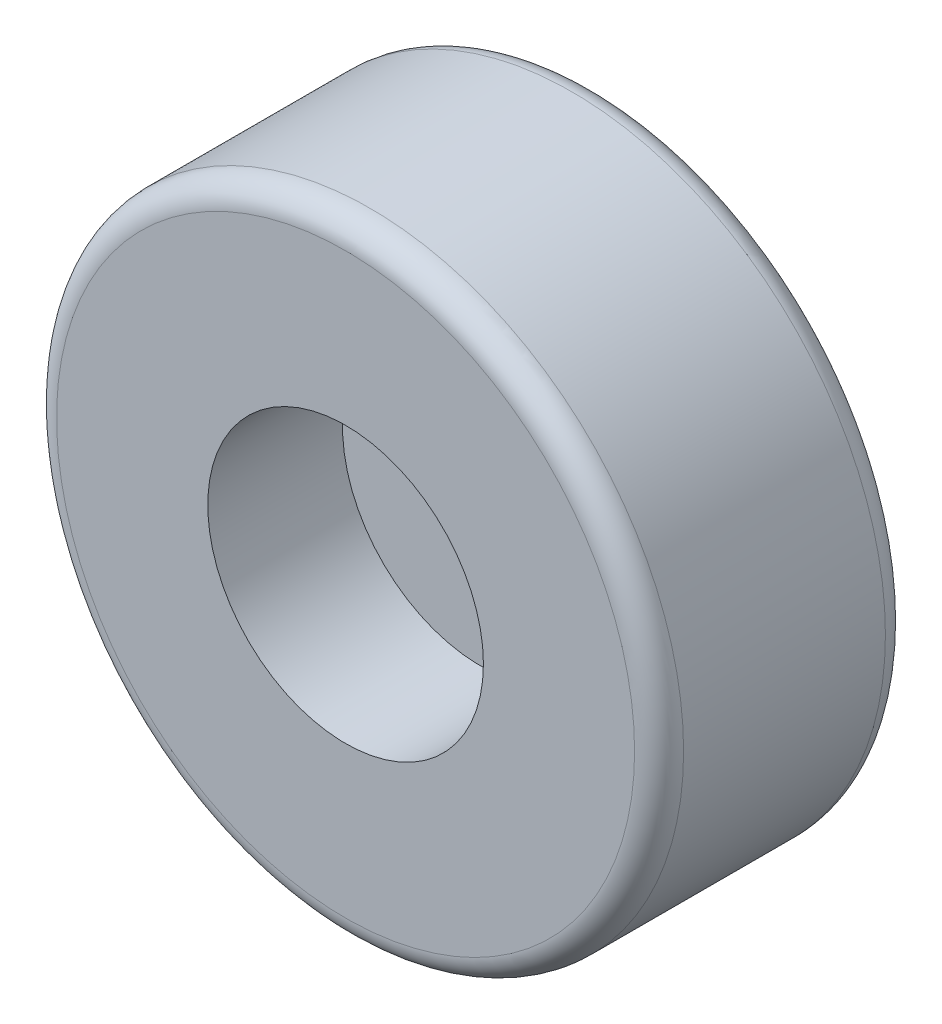
SolidWorks part; units mm, degrees
material "Rubber"
ref_plane "Front Plane" through (0, 0, 0) normal (0, 0, 1) x (1, 0, 0)
ref_plane "Top Plane" through (0, 0, 0) normal (0, 1, 0) x (1, 0, 0)
ref_plane "Right Plane" through (0, 0, 0) normal (1, 0, 0) x (0, 0, -1)
sketch "Sketch1" plane through (0, 0, 0) normal (0, 0, 1) x (1, 0, 0)
  circle A0 centre (0, 0) radius 32.5
  dimension "D1" = 65
extrude "Boss-Extrude1" add sketch "Sketch1" along normal blind 26
fillet "Fillet1" radius 2.54 2 edges at (32.5, 0, 0) (32.5, 0, 26)
sketch "Sketch2" plane through (0, 0, 26) normal (0, 0, 1) x (1, 0, 0)
  circle A0 centre (0, 0) radius 3.1115
  dimension "D1" = 6.223
extrude "Cut-Extrude1" cut sketch "Sketch2" against normal up to surface (26 mm away) up to face at (29.96, 0, 0)
sketch "Sketch3" plane through (0, 0, 26) normal (0, 0, 1) x (1, 0, 0)
  circle A0 centre (0, 0) radius 14.2875
  dimension "D1" = 28.575
extrude "Cut-Extrude2" cut sketch "Sketch3" against normal blind 13.97
